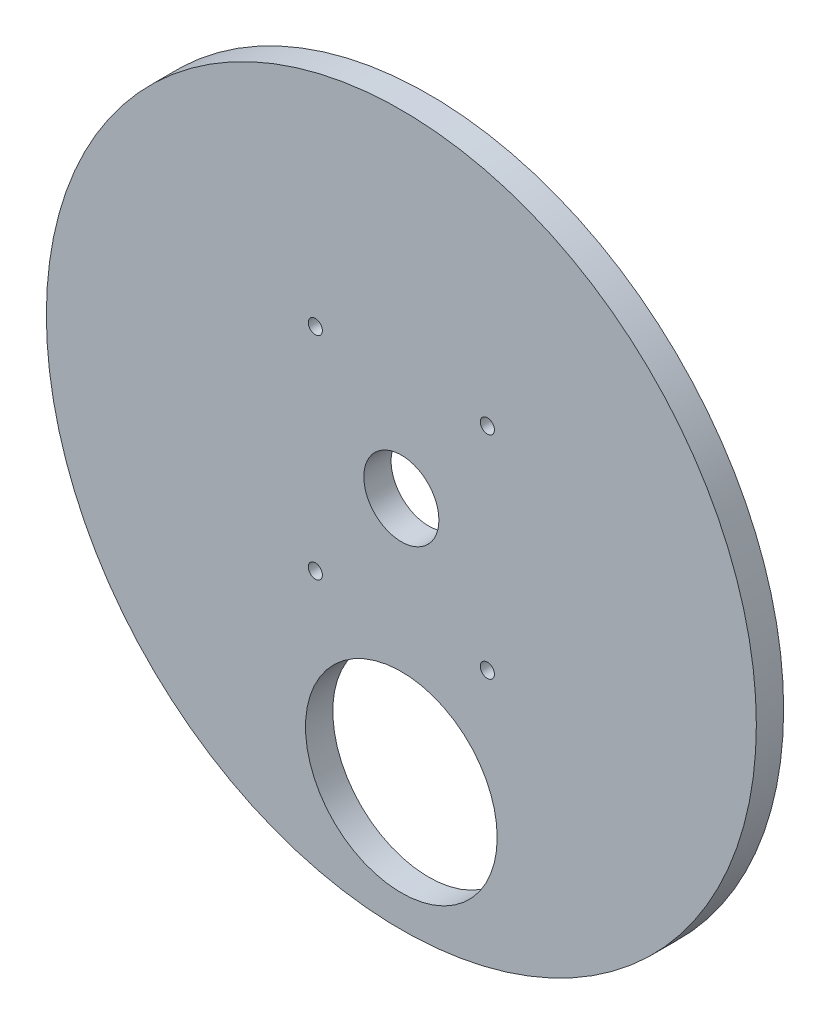
SolidWorks part; units mm, degrees
ref_plane "Front Plane" through (0, 0, 0) normal (0, 0, 1) x (1, 0, 0)
ref_plane "Top Plane" through (0, 0, 0) normal (0, 1, 0) x (1, 0, 0)
ref_plane "Right Plane" through (0, 0, 0) normal (1, 0, 0) x (0, 0, -1)
sketch "Sketch1" plane through (0, 0, 0) normal (0, 0, 1) x (1, 0, 0)
  line L0 (0, 0) -> (0, -50000) construction
  circle A0 centre (0, -46.743) radius 127
  circle A1 centre (0, -8.643) radius 165.1
  circle A3 centre (0, -114.3) radius 44.577
  circle A7 centre (0, 0) radius 17.4625
  point P4 (0, -173.743)
  point P12 (0, 0)
  point P16 (0, 0)
  point P76 (0, 0)
  dimension "D1" = 114.3
  dimension "D4" = 89.154
  dimension "D5" = 67.557
  dimension "D6" = 330.2
  dimension "D2" = 34.925
  dimension "D3" = 254
extrude "Boss-Extrude1" add sketch "Sketch1" along normal blind 12.7 contours A1 L0 A0 | A0 L0 A7 A3 | L0 A0 A3 A7 | L0 A1 A0
sketch "Sketch9" plane through (0, 0, 0) normal (0, 0, 1) x (1, 0, 0)
  line L1 (-40.005, 49.2125) -> (40.005, 49.2125)
  line L2 (-40.005, 49.2125) -> (-40.005, -147.6375)
  line L3 (-40.005, -147.6375) -> (40.005, -147.6375)
  line L4 (40.005, 49.2125) -> (40.005, -147.6375)
  circle A3 centre (-40.005, -49.2125) radius 3.175
  circle A4 centre (-40.005, 49.2125) radius 3.175
  circle A5 centre (40.005, 49.2125) radius 3.175
  circle A6 centre (40.005, -49.2125) radius 3.175
  point P4 (0, 49.2125)
  dimension "D1" = 49.2125
  dimension "D2" = 40.005
  dimension "D5" = 98.425
  dimension "D6" = 6.35
  dimension "D3" = 196.85
hole_wizard "CBORE for 1/4 Hex Head Bolt1" positions "Sketch11" profile "Sketch10" counterbore size "1/4" standard "ANSI Inch"
sketch "Sketch11" plane through (0, 0, 0) normal (0, 0, -1) x (-1, 0, 0)
  point P0 (-40.005, 49.2125)
  point P3 (40.005, 49.2125)
  point P6 (40.005, -49.2125)
  point P9 (-40.005, -49.2125)
  dimension "D1" = 98.425
  dimension "D2" = 40.005
sketch "Sketch10" plane through (40.005, 49.2125, 0) normal (1, 0, 0) x (0, 1, 0)
  line L0 (0, 0) -> (0, 14.6754)
  line L1 (0, 14.6754) -> (3.2893, 12.699)
  line L2 (3.2893, 12.699) -> (3.2893, 3.81)
  line L3 (3.2893, 3.81) -> (6.35, 3.81)
  line L4 (6.35, 3.81) -> (6.35, 0)
  line L5 (6.35, 0) -> (0, 0)
  line L10 (0, 14.6754) -> (-3.2893, 12.699) construction
  line L11 (0, -6.35) -> (0, 107.95) construction
  dimension "Hole Dia." = 6.5786
  dimension "Hole Depth" = 12.699
  dimension "C'Bore Dia." = 12.7
  dimension "C'Bore Depth" = 3.81
  dimension "Drill Angle" = 118
